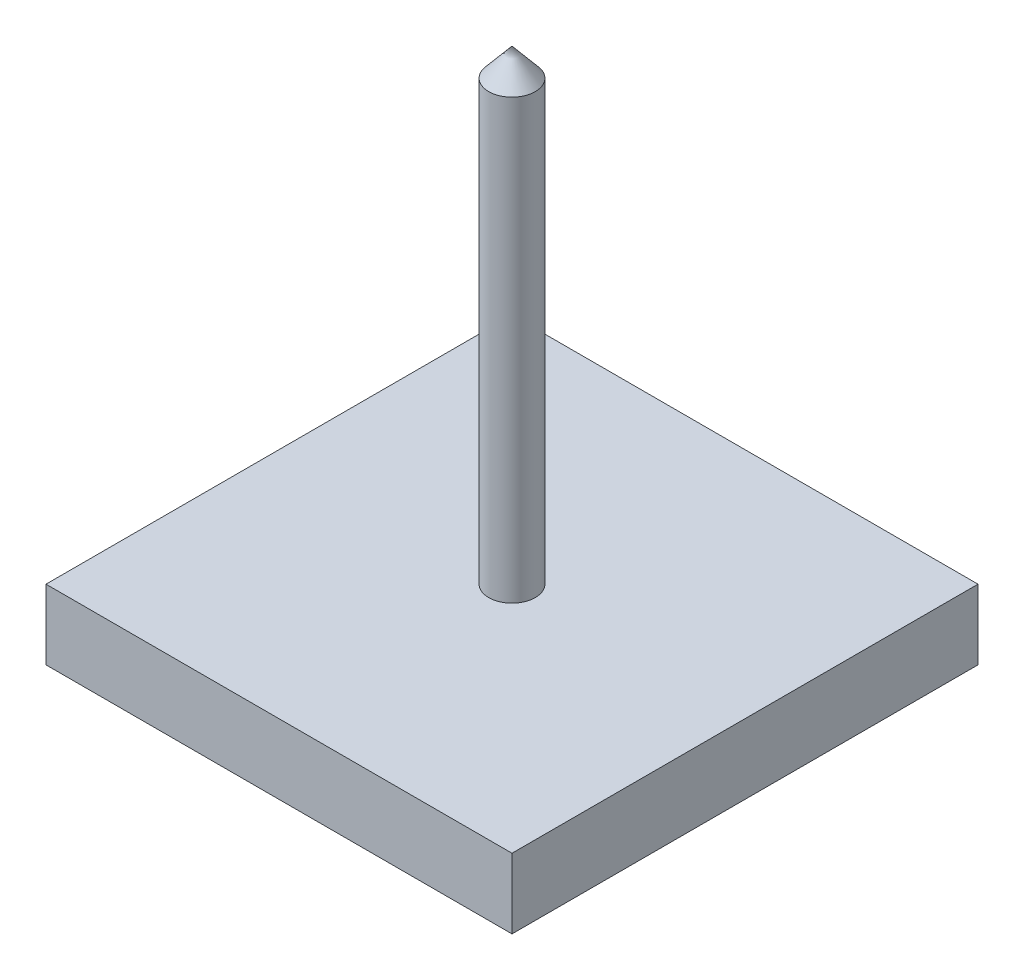
SolidWorks part; units mm, degrees
ref_plane "Alzado" through (0, 0, 0) normal (0, 0, 1) x (1, 0, 0)
ref_plane "Planta" through (0, 0, 0) normal (0, 1, 0) x (1, 0, 0)
ref_plane "Vista lateral" through (0, 0, 0) normal (1, 0, 0) x (0, 0, -1)
sketch "Croquis1" plane through (0, 0, 0) normal (0, 1, 0) x (1, 0, 0)
  line L1 (0, 0) -> (20, 0)
  line L2 (0, 0) -> (0, 20)
  line L3 (0, 20) -> (20, 20)
  line L4 (20, 0) -> (20, 20)
  dimension "D1" = 20
extrude "Saliente-Extruir1" add sketch "Croquis1" along normal blind 3
ref_plane "Plano1" through (10, 0, 0) normal (1, 0, 0) x (0, 0, -1)
sketch "Croquis2" plane through (10, 0, 0) normal (1, 0, 0) x (0, 0, -1)
  line L0 (10, 3) -> (10, 23)
  line L1 (0, 3) -> (20, 3) construction
  line L2 (10, 23) -> (11, 21.8082)
  line L3 (11, 21.8082) -> (11, 3)
  line L4 (11, 3) -> (10, 3)
  dimension "D1" = 20
  dimension "D2" = 1
  dimension "D3" = 40
revolve "Revolución1" add sketch "Croquis2" angle 360 about L0
